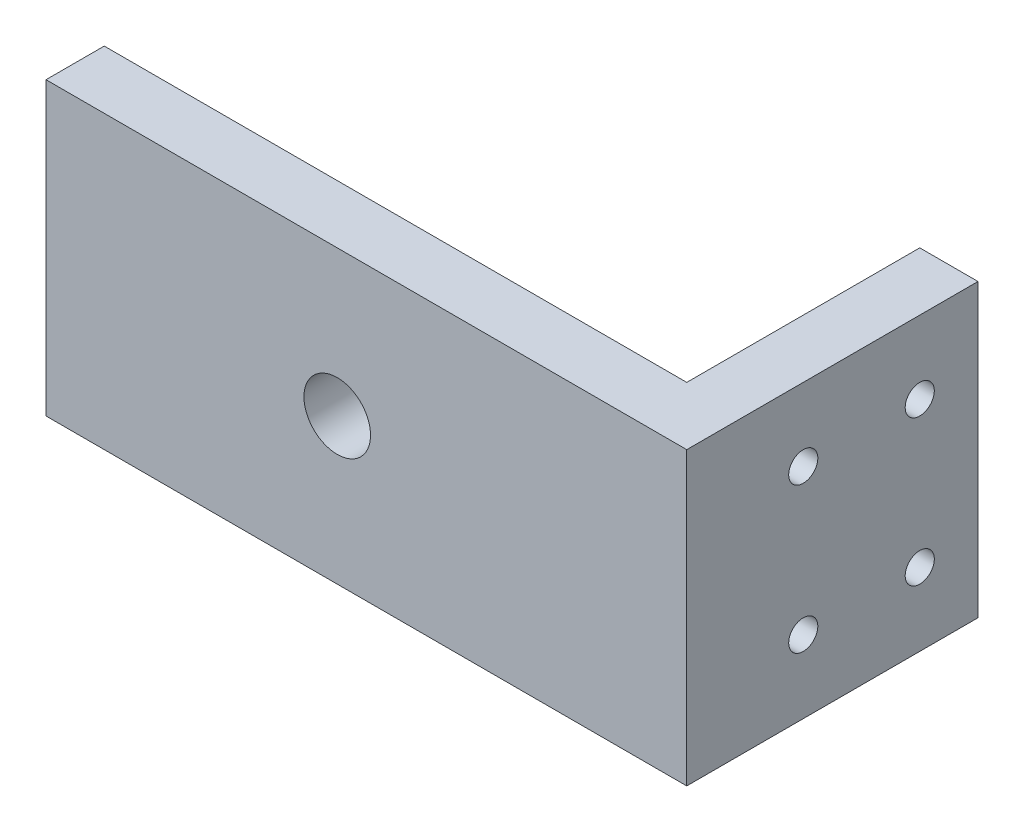
SolidWorks part; units mm, degrees
ref_plane "Front Plane" through (0, 0, 0) normal (0, 0, 1) x (1, 0, 0)
ref_plane "Top Plane" through (0, 0, 0) normal (0, 1, 0) x (1, 0, 0)
ref_plane "Right Plane" through (0, 0, 0) normal (1, 0, 0) x (0, 0, -1)
sketch "Sketch2" plane through (0, 0, 0) normal (0, 1, 0) x (1, 0, 0)
  line L0 (0, 0) -> (110, 0)
  line L1 (110, 0) -> (110, 50)
  line L2 (110, 50) -> (100, 50)
  line L3 (100, 50) -> (100, 10)
  line L4 (100, 10) -> (0, 10)
  line L5 (0, 10) -> (0, 0)
  dimension "D1" = 100
  dimension "D2" = 10
  dimension "D3" = 50
extrude "Boss-Extrude1" add sketch "Sketch2" along normal blind 50 contours L4 L5 L0 L1 L2 L3
sketch "Sketch3" plane through (0, 0, -10) normal (0, 0, -1) x (-1, 0, 0)
  circle A0 centre (-50, 25) radius 5.7165
extrude "Cut-Extrude1" cut sketch "Sketch3" against normal up to next contours A0
sketch "Sketch5" plane through (100, 0, 0) normal (-1, 0, 0) x (0, 0, 1)
  circle A0 centre (-40, 37.5) radius 2.5
  circle A1 centre (-20, 37.5) radius 2.5
  circle A2 centre (-20, 12.5) radius 2.5
  circle A3 centre (-40, 12.5) radius 2.5
  dimension "D1" = 5
extrude "Cut-Extrude2" cut sketch "Sketch5" against normal up to next contours A3 | A2 | A0 | A1
